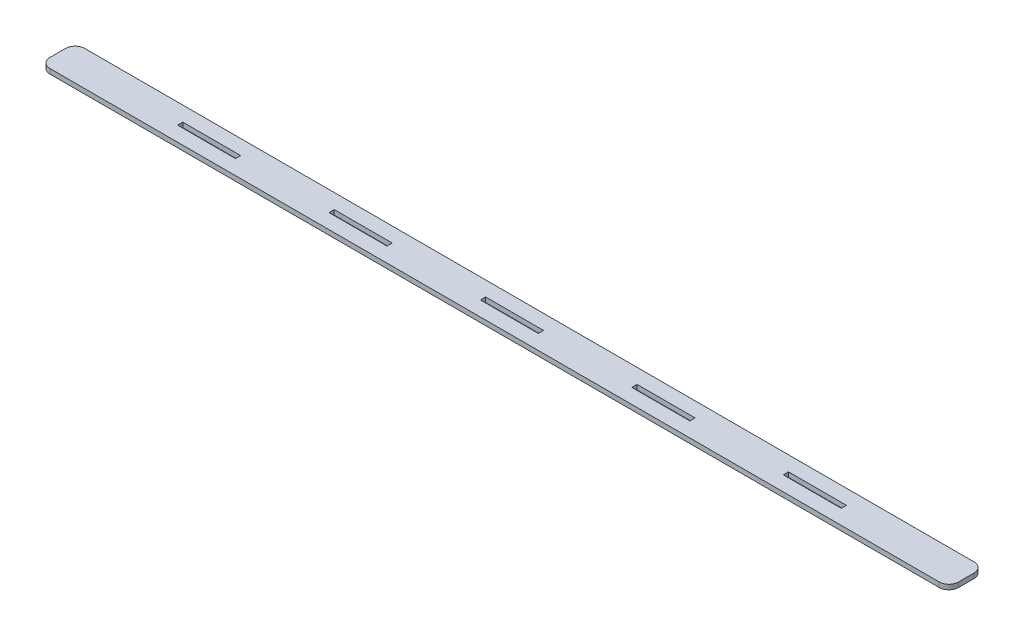
SolidWorks part; units mm, degrees
other "Markup1"
sketch "Sketch4" plane through (-298.45, 3.175, 19.05) normal (-0.3913, 0.9147, 0.101) x (0.9172, 0.3786, 0.1243)
material "Acrylic (Medium-high impact)"
ref_plane "Plan de face" through (0, 0, 0) normal (0, 0, 1) x (1, 0, 0)
ref_plane "Plan de dessus" through (0, 0, 0) normal (0, 1, 0) x (1, 0, 0)
ref_plane "Plan de droite" through (0, 0, 0) normal (1, 0, 0) x (0, 0, -1)
sketch "Sketch1" plane through (0, 0, 0) normal (0, 1, 0) x (1, 0, 0)
  line L1 (298.45, -11.43) -> (-298.45, -11.43)
  line L2 (298.45, -11.43) -> (298.45, 11.43)
  line L3 (298.45, 11.43) -> (-298.45, 11.43)
  line L4 (-298.45, -11.43) -> (-298.45, 11.43)
  line L5 (298.45, -11.43) -> (-298.45, 11.43) construction
  line L6 (298.45, 11.43) -> (-298.45, -11.43) construction
  point P0 (0, 0)
  dimension "D1" = 596.9
  dimension "D2" = 22.86
extrude "Boss-Extrude1" add sketch "Sketch1" along normal blind 3.175
sketch "Sketch5" plane through (0, 3.175, 0) normal (0, 1, 0) x (1, 0, 0)
  line L0 (-298.45, 0) -> (298.45, 0) construction
  line L1 (-218.0167, -1.7145) -> (-179.9167, -1.7145)
  line L2 (-218.0167, -1.7145) -> (-218.0167, 1.7145)
  line L3 (-218.0167, 1.7145) -> (-179.9167, 1.7145)
  line L4 (-179.9167, -1.7145) -> (-179.9167, 1.7145)
  line L5 (-218.0167, -1.7145) -> (-179.9167, 1.7145) construction
  line L6 (-218.0167, 1.7145) -> (-179.9167, -1.7145) construction
  line L7 (298.45, -11.43) -> (298.45, 11.43) construction
  line L8 (-298.45, 11.43) -> (-298.45, -11.43) construction
  line L10 (-118.5333, -1.7145) -> (-80.4333, -1.7145)
  line L11 (-118.5333, -1.7145) -> (-118.5333, 1.7145)
  line L12 (-118.5333, 1.7145) -> (-80.4333, 1.7145)
  line L13 (-80.4333, -1.7145) -> (-80.4333, 1.7145)
  line L14 (-118.5333, -1.7145) -> (-80.4333, 1.7145) construction
  line L15 (-118.5333, 1.7145) -> (-80.4333, -1.7145) construction
  line L16 (-19.05, -1.7145) -> (19.05, -1.7145)
  line L17 (-19.05, -1.7145) -> (-19.05, 1.7145)
  line L18 (-19.05, 1.7145) -> (19.05, 1.7145)
  line L19 (19.05, -1.7145) -> (19.05, 1.7145)
  line L20 (-19.05, -1.7145) -> (19.05, 1.7145) construction
  line L21 (-19.05, 1.7145) -> (19.05, -1.7145) construction
  line L22 (80.4333, -1.7145) -> (118.5333, -1.7145)
  line L23 (80.4333, -1.7145) -> (80.4333, 1.7145)
  line L24 (80.4333, 1.7145) -> (118.5333, 1.7145)
  line L25 (118.5333, -1.7145) -> (118.5333, 1.7145)
  line L26 (80.4333, -1.7145) -> (118.5333, 1.7145) construction
  line L27 (80.4333, 1.7145) -> (118.5333, -1.7145) construction
  line L28 (179.9167, -1.7145) -> (218.0167, -1.7145)
  line L29 (179.9167, -1.7145) -> (179.9167, 1.7145)
  line L30 (179.9167, 1.7145) -> (218.0167, 1.7145)
  line L31 (218.0167, -1.7145) -> (218.0167, 1.7145)
  line L32 (179.9167, -1.7145) -> (218.0167, 1.7145) construction
  line L33 (179.9167, 1.7145) -> (218.0167, -1.7145) construction
  point P0 (-198.9667, 0)
  point P8 (0, 0)
  point P9 (99.4833, 0)
  point P10 (-99.4833, 0)
  point P15 (-99.4833, 1.7145)
  point P25 (198.9667, 0)
  point P30 (0, 1.7145)
  point P32 (99.4833, 1.7145)
  point P35 (0, 0)
  point P36 (179.9167, 0)
  dimension "D1" = 3.429
  dimension "D2" = 99.4833
  dimension "D3" = 38.1
  dimension "D6" = 38.1
  dimension "D8" = 38.1
  dimension "D10" = 38.1
  dimension "D12" = 38.1
  dimension "D13" = 99.4833
  dimension "D14" = 99.4833
  dimension "D15" = 99.4833
  dimension "D16" = 99.4833
extrude "Cut-Extrude2" cut sketch "Sketch5" against normal through all
fillet "Fillet1" radius 6.35 4 edges at (298.45, 1.5875, 11.43) (298.45, 1.5875, -11.43) (-298.45, 1.5875, 11.43) (-298.45, 1.5875, -11.43)
